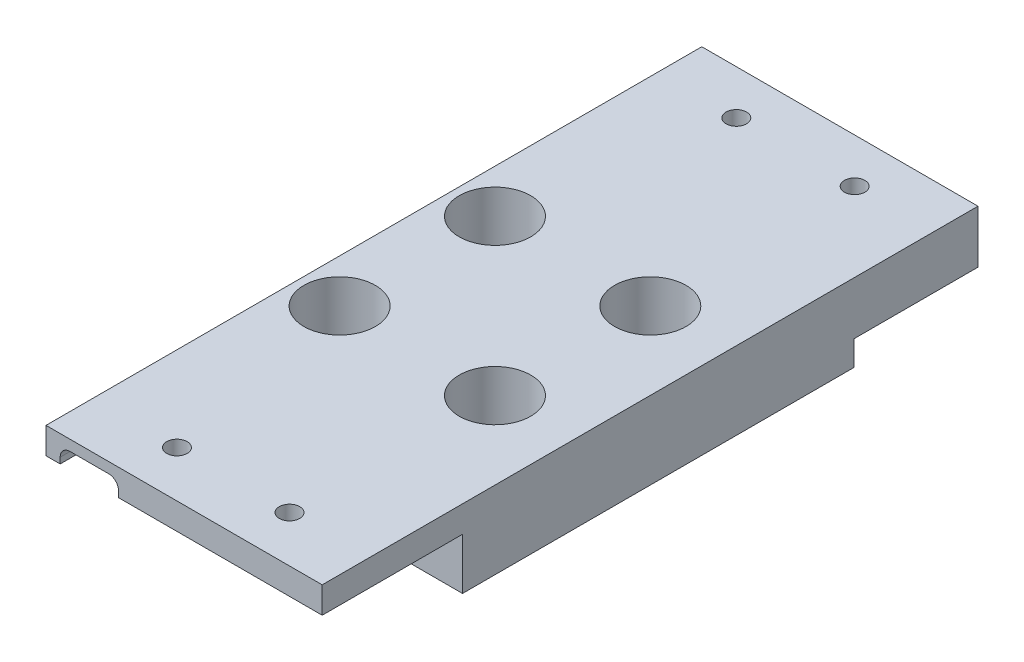
SolidWorks part; units mm, degrees
ref_plane "Front" through (0, 0, 0) normal (0, 0, 1) x (1, 0, 0)
ref_plane "Top" through (0, 0, 0) normal (0, 1, 0) x (1, 0, 0)
ref_plane "Right" through (0, 0, 0) normal (1, 0, 0) x (0, 0, -1)
sketch "Sketch1" plane through (0, 0, 0) normal (0, 1, 0) x (1, 0, 0)
  line L0 (0, 26.3852) -> (0, -26.3852) construction
  line L1 (-22.225, 26.3852) -> (22.225, 26.3852)
  line L2 (-22.225, 26.3852) -> (-22.225, -26.3852)
  line L3 (-22.225, -26.3852) -> (22.225, -26.3852)
  line L4 (22.225, 26.3852) -> (22.225, -26.3852)
  dimension "D1" = 44.45
  dimension "D2" = 52.7705
extrude "Extrude1" add sketch "Sketch1" along normal blind 12.5
hole_wizard "M4x0.7 Tapped Hole2" positions "Sketch3" profile "Sketch2" tap size "M4x0.7" standard "Ansi Metric" end condition through all
sketch "Sketch3" plane through (0, 12.5, 0) normal (0, 1, 0) x (-1, 0, 0)
  line L0 (9.525, -19.2363) -> (-9.525, -19.2363) construction
  line L2 (0, -19.2363) -> (0, 1.3968) construction
  line L4 (-12.1031, -19.2363) -> (-6.9469, -19.2363) construction
  line L5 (-12.1031, -20.6206) -> (-12.1031, -17.852) construction
  line L6 (-6.9469, -17.852) -> (-6.9469, -20.6206) construction
  line L8 (-9.525, -19.2363) -> (-9.525, -20.6206) construction
  point P0 (9.525, -19.2363)
  point P1 (-9.525, -19.2363)
sketch "Sketch2" plane through (-9.525, 12.5, -19.2363) normal (1, 0, 0) x (0, 0, 1)
  line L0 (0, 0) -> (0, 12.5)
  line L1 (0, 12.5) -> (1.65, 12.5)
  line L2 (1.65, 12.5) -> (1.65, 0)
  line L5 (1.65, 0) -> (0, 0)
  line L11 (0, -6.35) -> (0, 107.95) construction
  dimension "Thread Major Dia." = 3.3
  dimension "Thru Tap Drill Depth" = 12.5
hole_wizard "CBORE for M6 SBHCS1" positions "Sketch5" profile "Sketch4" counterbore size "M6" standard "Ansi Metric" end condition through all
sketch "Sketch5" plane through (0, 12.5, 0) normal (0, 1, 0) x (-1, 0, 0)
  line L0 (15.24, 13.8852) -> (-9.76, 13.8852) construction
  line L4 (22.225, 26.3852) -> (-22.225, 26.3852) construction
  line L5 (22.225, -26.3852) -> (22.225, 26.3852) construction
  point P0 (15.24, 13.8852)
  point P1 (-9.76, 13.8852)
  dimension "D1" = 25
  dimension "D2" = 12.5
  dimension "D3" = 6.985
sketch "Sketch4" plane through (-15.24, 12.5, 13.8852) normal (1, 0, 0) x (0, 0, 1)
  line L0 (0, 0) -> (0, 12.5)
  line L1 (0, 12.5) -> (3.3, 12.5)
  line L3 (3.3, 12.5) -> (3.3, 8.3)
  line L4 (3.3, 8.3) -> (5.75, 8.3)
  line L5 (5.75, 8.3) -> (5.75, 0)
  line L7 (5.75, 0) -> (0, 0)
  line L11 (0, -6.35) -> (0, 107.95) construction
  dimension "Thru Hole Dia." = 6.6
  dimension "Thru Hole Depth" = 12.5
  dimension "C'Bore Dia." = 11.5
  dimension "C'Bore Depth" = 8.3
mirror "Mirror1" about plane through (-22.225, 12.5, 26.3852) normal (0, 0, -1) of "Extrude1", "CBORE for M6 SBHCS1"
sketch "Sketch6" plane through (0, 0, 0) normal (0, -1, 0) x (1, 0, 0)
  line L0 (-22.225, -26.3852) -> (-22.225, 79.1557) construction
  line L1 (22.225, 79.1557) -> (-22.225, 79.1557)
  line L2 (22.225, 79.1557) -> (22.225, 56.5724)
  line L3 (22.225, 56.5724) -> (-22.225, 56.5724)
  line L4 (-22.225, 79.1557) -> (-22.225, 56.5724)
extrude "Extrude2" cut sketch "Sketch6" against normal blind 8.255
ref_point "Point1"
ref_plane "Plane1" through (0, 0, 26.3852) normal (0, 0, 1) x (1, 0, 0)
sketch "Sketch7" plane through (0, 0, 0) normal (0, -1, 0) x (1, 0, 0)
  line L0 (-22.225, -26.3852) -> (-22.225, 56.5724) construction
  line L1 (22.225, -26.3852) -> (-22.225, -26.3852)
  line L2 (22.225, -26.3852) -> (22.225, -6.41)
  line L3 (22.225, -6.41) -> (-22.225, -6.41)
  line L4 (-22.225, -26.3852) -> (-22.225, -6.41)
  dimension "D1" = 19.9753
extrude "Extrude3" cut sketch "Sketch7" against normal blind 4
sketch "Sketch8" plane through (0, 8.255, 0) normal (0, -1, 0) x (1, 0, 0)
  line L0 (22.225, 79.1557) -> (-22.225, 79.1557) construction
  line L1 (-10.5442, 79.1557) -> (-19.9422, 79.1557)
  line L2 (-10.5442, 79.1557) -> (-10.5442, 56.5724)
  line L3 (-10.5442, 56.5724) -> (-19.9422, 56.5724)
  line L4 (-19.9422, 79.1557) -> (-19.9422, 56.5724)
  line L5 (-22.225, 56.5724) -> (22.225, 56.5724) construction
  line L6 (-15.2432, 79.1557) -> (-15.2432, 56.5724) construction
  line L7 (-22.225, -6.41) -> (-22.225, 56.5724) construction
  dimension "D1" = 9.398
  dimension "D2" = 6.9818
extrude "Cut-Extrude1" cut sketch "Sketch8" against normal blind 2.54
fillet "Fillet1" radius 1.5875 5 edges at (-10.5442, 10.795, 67.8641) (-15.2432, 10.795, 56.5724) (-19.9422, 10.795, 67.8641) (-19.9422, 9.525, 56.5724) (-10.5442, 9.525, 56.5724)
hole_wizard "M4x0.7 Tapped Hole3" positions "Sketch10" profile "Sketch9" tap size "M4x0.7" standard "Ansi Metric" end condition through all
sketch "Sketch10" plane through (0, 12.5, 0) normal (0, 1, 0) x (-1, 0, 0)
  line L0 (-12.1031, 71.7115) -> (-6.9469, 71.7115) construction
  point P0 (-9.525, 71.7115)
  point P1 (8.5969, 71.7115)
  dimension "D1" = 18.1219
sketch "Sketch9" plane through (9.525, 12.5, 71.7115) normal (1, 0, 0) x (0, 0, 1)
  line L0 (0, 0) -> (0, 12.5)
  line L1 (0, 12.5) -> (1.65, 12.5)
  line L2 (1.65, 12.5) -> (1.65, 0)
  line L5 (1.65, 0) -> (0, 0)
  line L11 (0, -6.35) -> (0, 107.95) construction
  dimension "Thread Major Dia." = 3.3
  dimension "Thru Tap Drill Depth" = 12.5
